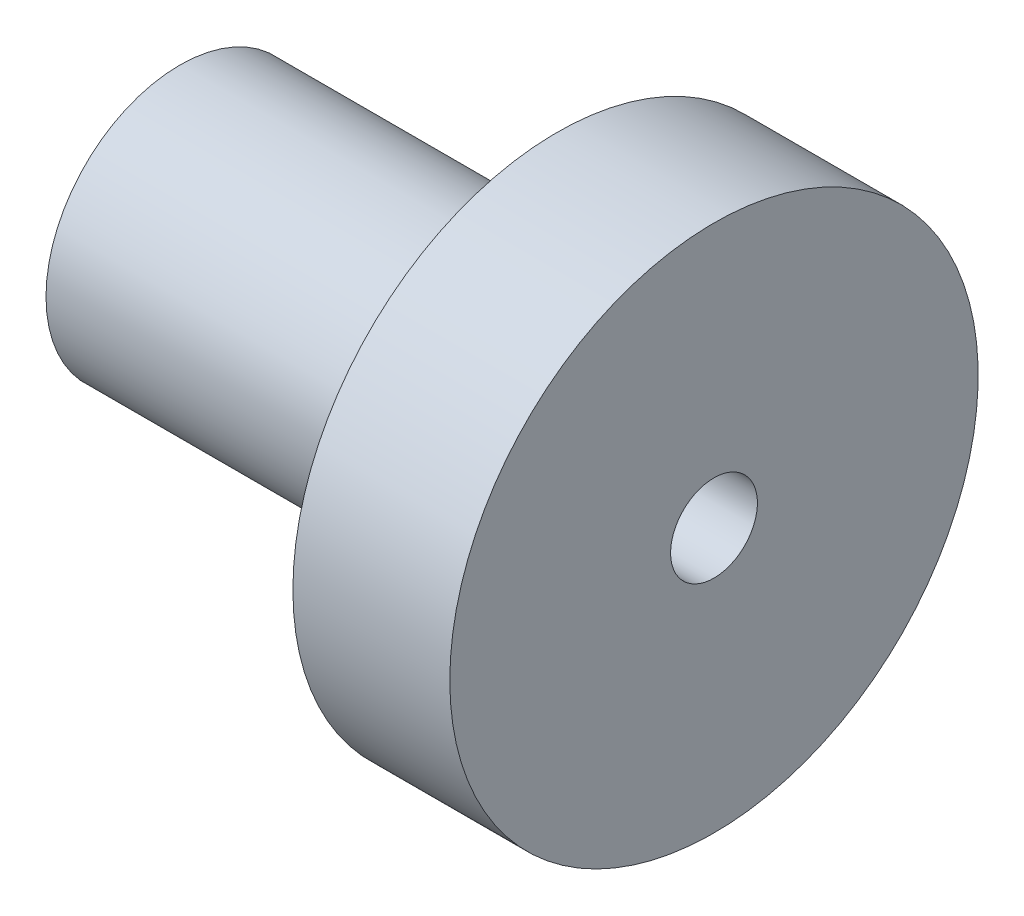
SolidWorks part; units mm, degrees
ref_plane "前视基准面" through (0, 0, 0) normal (0, 0, 1) x (1, 0, 0)
ref_plane "上视基准面" through (0, 0, 0) normal (0, 1, 0) x (1, 0, 0)
ref_plane "右视基准面" through (0, 0, 0) normal (1, 0, 0) x (0, 0, -1)
sketch "草图1" plane through (0, 0, 0) normal (0, 0, 1) x (1, 0, 0)
  line L0 (67.7262, 47.4291) -> (67.7262, 24.0252)
  line L1 (0, 0) -> (67.7262, 0)
  line L2 (0, 0) -> (0, 24.0252)
  line L3 (0, 24.0252) -> (67.7262, 24.0252)
  line L5 (67.7262, 0) -> (95.8937, 0)
  line L7 (67.7262, 47.4291) -> (95.8937, 47.4291)
  line L8 (95.8937, 0) -> (95.8937, 47.4291)
revolve "旋转1" add sketch "草图1" angle 360 about L1
sketch "草图2" plane through (0, 0, 0) normal (-1, 0, 0) x (0, 0, 1)
  circle A0 centre (0, 0) radius 7.7959
extrude "切除-拉伸1" cut sketch "草图2" against normal through all
